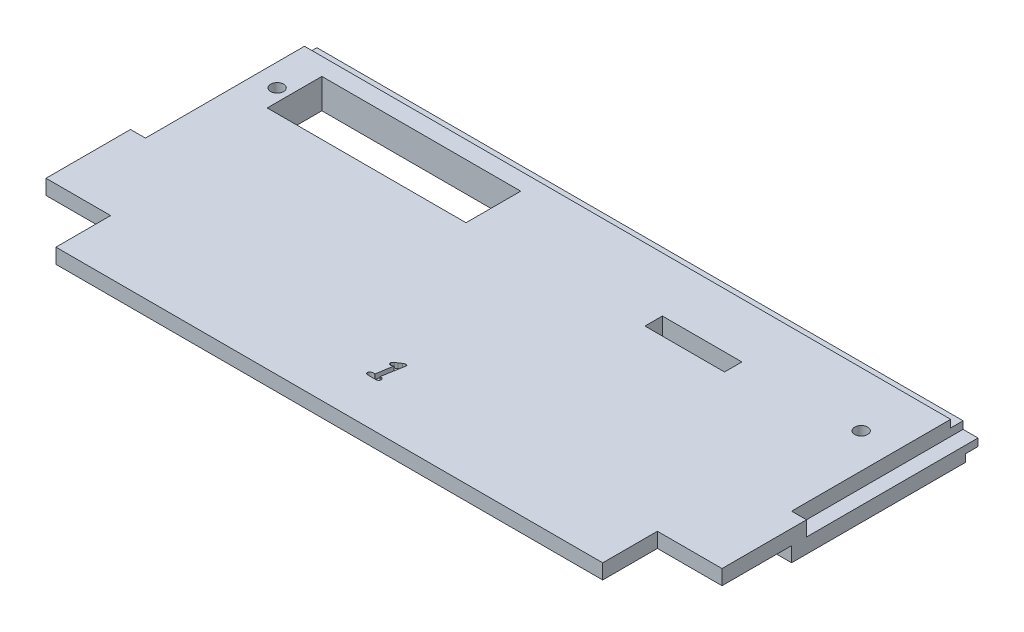
SolidWorks part; units mm, degrees
material "ABS"
ref_plane "前基準面" through (0, 0, 0) normal (0, 0, 1) x (1, 0, 0)
ref_plane "上基準面" through (0, 0, 0) normal (0, 1, 0) x (1, 0, 0)
ref_plane "右基準面" through (0, 0, 0) normal (1, 0, 0) x (0, 0, -1)
sketch "草圖1" plane through (0, 0, 0) normal (0, 0, 1) x (1, 0, 0)
  line L1 (-102.0286, 1.9929) -> (7.9714, 1.9929)
  line L2 (-102.0286, 1.9929) -> (-102.0286, -1.0071)
  line L3 (-102.0286, -1.0071) -> (7.9714, -1.0071)
  line L4 (7.9714, 1.9929) -> (7.9714, -1.0071)
  dimension "D1" = 3
  dimension "D2" = 110
extrude "填料-伸長1" add sketch "草圖1" along normal blind 11
sketch "草圖2" plane through (0, 0, 0) normal (0, 0, -1) x (-1, 0, 0)
  line L0 (102.0286, -1.0071) -> (-7.9714, -1.0071) construction
  line L1 (115.0286, -1.0071) -> (-20.9714, -1.0071)
  line L2 (115.0286, -1.0071) -> (115.0286, 1.9929)
  line L3 (115.0286, 1.9929) -> (-20.9714, 1.9929)
  line L4 (-20.9714, -1.0071) -> (-20.9714, 1.9929)
  line L5 (-7.9714, 1.9929) -> (102.0286, 1.9929) construction
  line L6 (-7.9714, -1.0071) -> (-7.9714, 1.9929) construction
  line L7 (102.0286, 1.9929) -> (102.0286, -1.0071) construction
  dimension "D1" = 13
  dimension "D2" = 13
extrude "填料-伸長2" add sketch "草圖2" along normal blind 14
sketch "草圖3" plane through (0, 0, -14) normal (0, 0, -1) x (-1, 0, 0)
  line L0 (115.0286, -1.0071) -> (115.0286, 1.9929) construction
  line L1 (-20.9714, 1.9929) -> (115.0286, 1.9929)
  line L2 (-20.9714, 1.9929) -> (-20.9714, -4.0071)
  line L3 (-20.9714, -4.0071) -> (115.0286, -4.0071)
  line L4 (115.0286, 1.9929) -> (115.0286, -4.0071)
  line L5 (-20.9714, -1.0071) -> (115.0286, -1.0071) construction
  dimension "D1" = 3
extrude "填料-伸長3" add sketch "草圖3" along normal blind 3
sketch "草圖4" plane through (0, 0, -17) normal (0, 0, -1) x (-1, 0, 0)
  line L0 (-20.9714, 1.9929) -> (-20.9714, -4.0071) construction
  line L1 (115.0286, -4.0071) -> (-20.9714, -4.0071)
  line L2 (115.0286, -4.0071) -> (115.0286, -1.0071)
  line L3 (115.0286, -1.0071) -> (-20.9714, -1.0071)
  line L4 (-20.9714, -4.0071) -> (-20.9714, -1.0071)
  line L5 (115.0286, 1.9929) -> (-20.9714, 1.9929) construction
  line L6 (112.0286, -1.0071) -> (-17.9714, -1.0071)
  line L7 (112.0286, -1.0071) -> (112.0286, 1.9929)
  line L8 (112.0286, 1.9929) -> (-17.9714, 1.9929)
  line L9 (-17.9714, -1.0071) -> (-17.9714, 1.9929)
  line L10 (115.0286, -4.0071) -> (115.0286, 1.9929) construction
  line M2 (-20.9714, 1.9929) -> (-20.9714, -4.0071)
  line M3 (-20.9714, -4.0071) -> (115.0286, -4.0071)
  line M4 (115.0286, -4.0071) -> (115.0286, 1.9929)
  line M5 (115.0286, 1.9929) -> (-20.9714, 1.9929)
  dimension "D1" = 3
  dimension "D2" = 3
  dimension "D3" = 3
extrude "填料-伸長4" add sketch "草圖4" along normal blind 32 contours L3 M4 M2 M3 | L9 L3 L7 M5
sketch "草圖5" plane through (0, 1.9929, 0) normal (0, 1, 0) x (1, 0, 0)
  text T0 " \r\n\r\n                  1               " font "Comic Sans MS" height in points 20
extrude "除料-伸長1" cut sketch "草圖5" against normal blind 1
sketch "草圖7" plane through (20.9714, 0, 0) normal (1, 0, 0) x (0, 0, -1)
  line L0 (49, -1.0071) -> (49, -4.0071) construction
  line L1 (49, -2.5071) -> (51.5, -2.5071)
  line L2 (49, -2.5071) -> (49, 0.4929)
  line L3 (49, 0.4929) -> (51.5, 0.4929)
  line L4 (51.5, -2.5071) -> (51.5, 0.4929)
  line L5 (49, -4.0071) -> (14, -4.0071) construction
  line L6 (49, 1.9929) -> (17, 1.9929) construction
  dimension "D1" = 1.5
  dimension "D2" = 1.5
  dimension "D3" = 2.5
extrude "填料-伸長5" add sketch "草圖7" against normal up to surface (136 mm away) up to face at (-115.0286, -1.0071, -20)
sketch "草圖8" plane through (0, 0, -49) normal (0, 0, 1) x (1, 0, 0)
  line L1 (-112.0286, -1.0071) -> (-115.0286, -1.0071)
  line L2 (-112.0286, -1.0071) -> (-112.0286, 0.4929)
  line L3 (-112.0286, 0.4929) -> (-115.0286, 0.4929)
  line L4 (-115.0286, -1.0071) -> (-115.0286, 0.4929)
extrude "除料-伸長2" cut sketch "草圖8" along direction (0, 0, -1) on the side against the normal up to next (2.5 mm away)
sketch "草圖9" plane through (0, 0, -49) normal (0, 0, 1) x (1, 0, 0)
  line L0 (20.9714, 0.4929) -> (20.9714, -1.0071) construction
  line L1 (17.9714, 0.4929) -> (20.9714, 0.4929)
  line L2 (17.9714, 0.4929) -> (17.9714, -1.0071)
  line L3 (17.9714, -1.0071) -> (20.9714, -1.0071)
  line L4 (20.9714, 0.4929) -> (20.9714, -1.0071)
extrude "除料-伸長3" cut sketch "草圖9" against normal up to surface (2.5 mm away) up to face at (-68.6952, -1.0071, -51.5)
sketch "草圖10" plane through (0, 1.9929, 0) normal (0, 1, 0) x (1, 0, 0)
  line L0 (-112.0286, 51.5) -> (-112.0286, 17) construction
  line L1 (17.9714, 49) -> (17.9714, 17) construction
  line L2 (-112.0286, 49) -> (17.9714, 49) construction
  circle A0 centre (-107.5286, 39) radius 1.3
  circle A1 centre (10.9714, 38) radius 1.3
  dimension "D1" = 2.6
  dimension "D2" = 2.6
  dimension "D7" = 11
  dimension "D3" = 4.5
  dimension "D4" = 7
  dimension "D6" = 10
extrude "除料-伸長4" cut sketch "草圖10" against normal up to next
sketch "草圖11" plane through (0, 1.9929, 0) normal (0, 1, 0) x (1, 0, 0)
  line L1 (-105.0286, 45.5) -> (-65.0286, 45.5)
  line L2 (-105.0286, 45.5) -> (-105.0286, 34.5)
  line L3 (-105.0286, 34.5) -> (-65.0286, 34.5)
  line L4 (-65.0286, 45.5) -> (-65.0286, 34.5)
  line L5 (-29.0286, 38) -> (-13.0286, 38)
  line L6 (-29.0286, 38) -> (-29.0286, 34.5)
  line L7 (-29.0286, 34.5) -> (-13.0286, 34.5)
  line L8 (-13.0286, 38) -> (-13.0286, 34.5)
  circle A0 centre (-107.5286, 39) radius 1.3 construction
  circle A1 centre (10.9714, 38) radius 1.3 construction
  point P6 (-105.0286, 40)
  dimension "D1" = 2.5
  dimension "D2" = 42.5
  dimension "D4" = 4.5
  dimension "D3" = 11
  dimension "D5" = 24
  dimension "D6" = 40
  dimension "D7" = 3.5
  dimension "D8" = 3.5
extrude "除料-伸長5" cut sketch "草圖11" against normal through all
